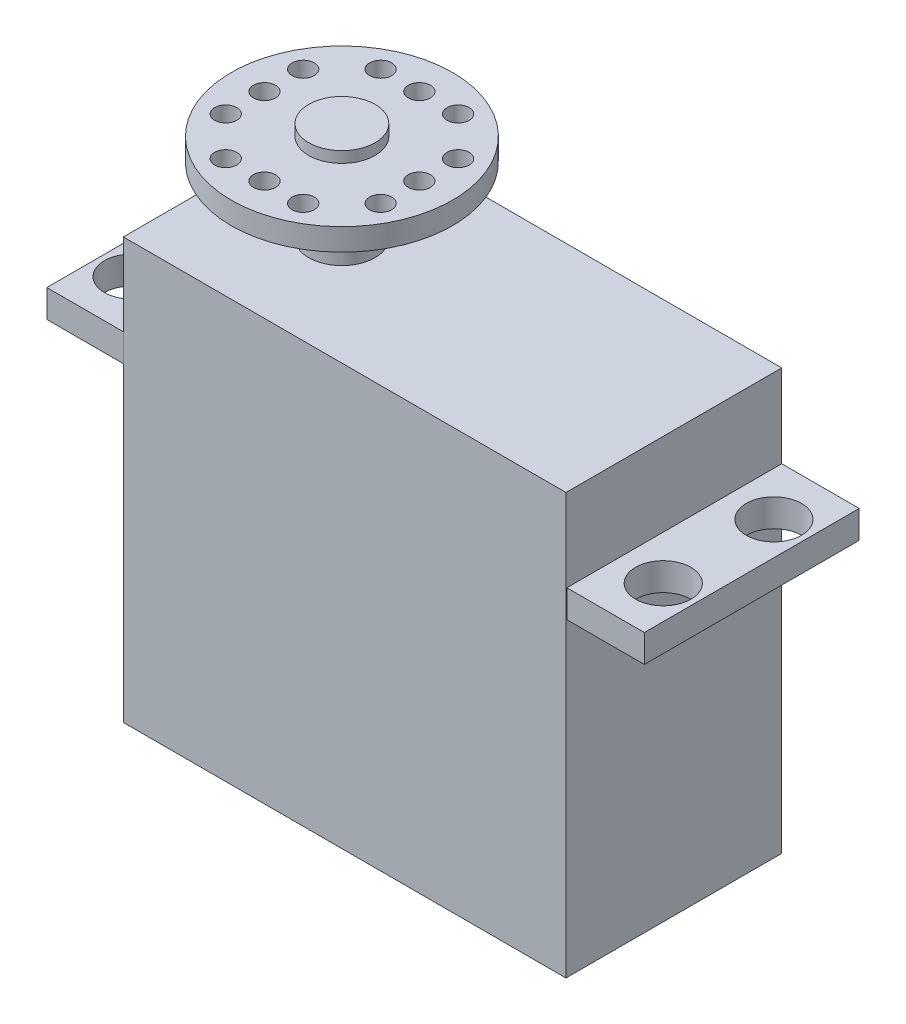
SolidWorks part; units mm, degrees
ref_plane "前视基准面" through (0, 0, 0) normal (0, 0, 1) x (1, 0, 0)
ref_plane "上视基准面" through (0, 0, 0) normal (0, 1, 0) x (1, 0, 0)
ref_plane "右视基准面" through (0, 0, 0) normal (1, 0, 0) x (0, 0, -1)
sketch "草图1" plane through (0, 0, 0) normal (0, 0, 1) x (1, 0, 0)
  line L1 (0, 0) -> (40, 0)
  line L2 (0, 0) -> (0, 38)
  line L3 (0, 38) -> (40, 38)
  line L4 (40, 0) -> (40, 38)
  dimension "D1" = 40
  dimension "D2" = 38
extrude "凸台-拉伸1" add sketch "草图1" along normal blind 19.5
sketch "草图2" plane through (0, 38, 0) normal (0, 1, 0) x (1, 0, 0)
  line L0 (20, 0) -> (20, -20.0013) construction
  line L1 (40, 0) -> (47, 0)
  line L2 (40, 0) -> (40, -19.4196)
  line L3 (40, -19.4196) -> (47, -19.4196)
  line L4 (47, 0) -> (47, -19.4196)
  line L5 (40, 0) -> (0, 0) construction
  line L6 (47, -9.7098) -> (40, -9.7098) construction
  line L7 (-7, -9.7098) -> (0, -9.7098) construction
  line L8 (-7, 0) -> (-7, -19.4196)
  line L9 (0, -19.4196) -> (-7, -19.4196)
  line L10 (0, 0) -> (0, -19.4196)
  line L11 (0, 0) -> (-7, 0)
  circle A0 centre (44, -4.7098) radius 2.5
  circle A1 centre (44, -14.7098) radius 2.5
  circle A2 centre (-4, -14.7098) radius 2.5
  circle A3 centre (-4, -4.7098) radius 2.5
  dimension "D2" = 5
  dimension "D4" = 10
  dimension "D1" = 7
  dimension "D3" = 4
extrude "凸台-拉伸2" add sketch "草图2" along normal blind 2.5 from offset 10 offset against normal yes
sketch "草图3" plane through (0, 38, 0) normal (0, 1, 0) x (1, 0, 0)
  line L0 (0, -9.75) -> (40, -9.75) construction
  line L1 (0, -19.5) -> (0, 0) construction
  line L2 (40, -19.5) -> (40, 0) construction
  circle A0 centre (10, -9.75) radius 3
  dimension "D1" = 10
  dimension "D2" = 6
extrude "凸台-拉伸3" add sketch "草图3" along normal blind 6
sketch "草图4" plane through (0, 44, 0) normal (0, 1, 0) x (1, 0, 0)
  line L0 (10, 0.25) -> (10, -23.899) construction
  line L1 (3, -2.75) -> (17, -2.75) construction
  line L2 (3, -2.75) -> (3, -16.75) construction
  line L3 (3, -16.75) -> (17, -16.75) construction
  line L4 (17, -2.75) -> (17, -16.75) construction
  line L5 (0, -9.75) -> (20, -9.75) construction
  line L6 (3, -16.75) -> (17, -2.75) construction
  circle A0 centre (10, -9.75) radius 10
  circle A1 centre (10, -2.75) radius 1
  circle A2 centre (13.5, -2.75) radius 1
  circle A3 centre (6.5, -2.75) radius 1
  circle A4 centre (6.5, -16.75) radius 1
  circle A5 centre (13.5, -16.75) radius 1
  circle A6 centre (10, -16.75) radius 1
  circle A7 centre (3, -13.25) radius 1
  circle A8 centre (3, -9.75) radius 1
  circle A9 centre (3, -6.25) radius 1
  circle A10 centre (17, -6.25) radius 1
  circle A11 centre (17, -9.75) radius 1
  circle A12 centre (17, -13.25) radius 1
  point P9 (10, -2.75)
  point P12 (17, -9.75)
  dimension "D1" = 20
  dimension "D4" = 3.5
  dimension "D5" = 3.5
  dimension "D6" = 2
  dimension "D7" = 2
  dimension "D8" = 2
  dimension "D2" = 14
  dimension "D3" = 14
extrude "凸台-拉伸4" add sketch "草图4" along normal blind 2
sketch "草图5" plane through (0, 46, 0) normal (0, 1, 0) x (1, 0, 0)
  circle A0 centre (10, -9.75) radius 3
  dimension "D1" = 6
extrude "凸台-拉伸5" add sketch "草图5" along normal blind 1
